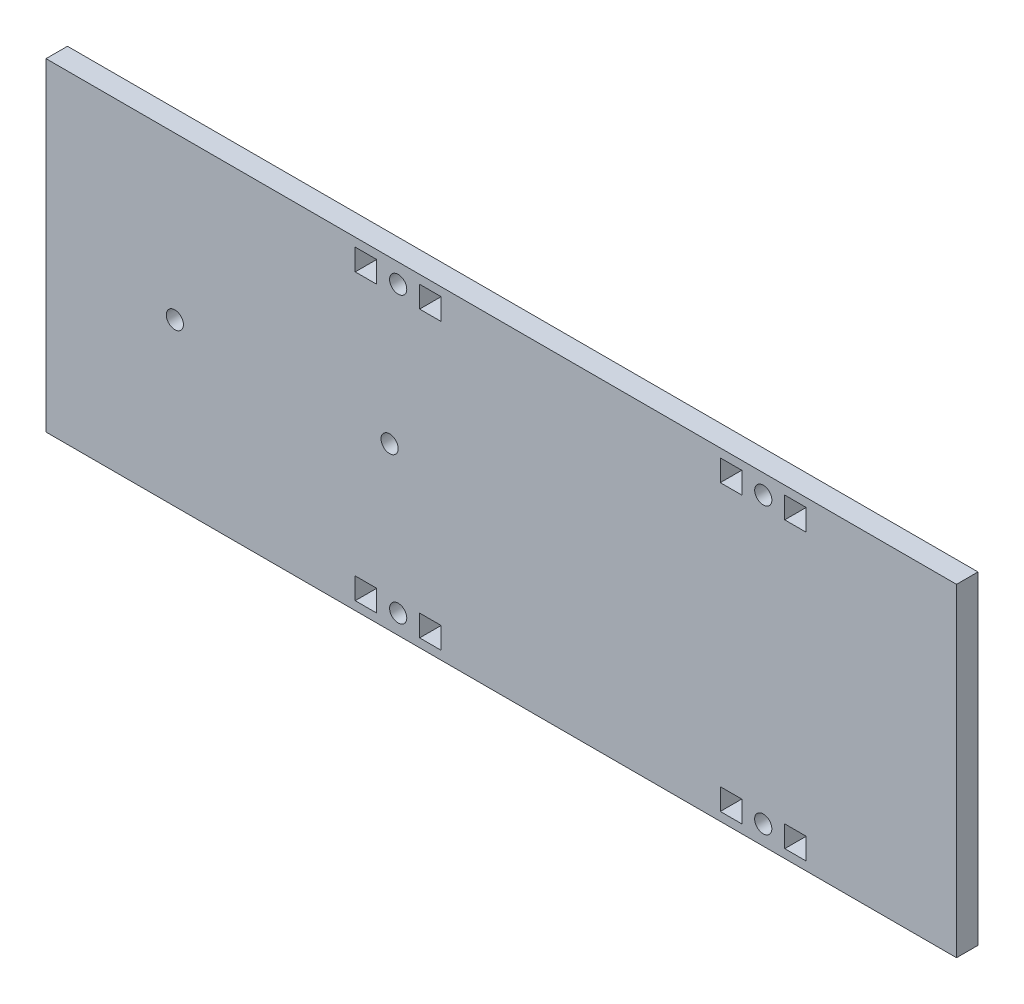
SolidWorks part; units mm, degrees
ref_plane "Plan de face" through (0, 0, 0) normal (0, 0, 1) x (1, 0, 0)
ref_plane "Plan de dessus" through (0, 0, 0) normal (0, 1, 0) x (1, 0, 0)
ref_plane "Plan de droite" through (0, 0, 0) normal (1, 0, 0) x (0, 0, -1)
sketch "Esquisse1" plane through (0, 0, 0) normal (0, 0, 1) x (1, 0, 0)
  line L0 (0, 0) -> (212, 0) construction
  line L1 (0, 37.65) -> (212, 37.65)
  line L2 (212, 37.65) -> (212, -37.65)
  line L3 (0, 37.65) -> (0, -37.65)
  line L4 (0, -37.65) -> (212, -37.65)
  circle A0 centre (30, 0) radius 2
  circle A1 centre (80, 0) radius 2
  point P11 (0, 0)
  line B0 (77, 33.15) -> (87, 33.15) construction
  line B1 (77, 35.65) -> (72, 35.65)
  line B2 (77, 35.65) -> (77, 30.65)
  line B3 (77, 30.65) -> (72, 30.65)
  line B4 (72, 35.65) -> (72, 30.65)
  line B5 (87, 35.65) -> (92, 35.65)
  line B6 (87, 35.65) -> (87, 30.65)
  line B7 (87, 30.65) -> (92, 30.65)
  line B8 (92, 35.65) -> (92, 30.65)
  line B9 (82, 33.15) -> (82, 40.1224) construction
  circle B10 centre (82, 33.15) radius 2
  line B11 (162, 33.15) -> (172, 33.15) construction
  line B12 (162, 35.65) -> (157, 35.65)
  line B13 (162, 35.65) -> (162, 30.65)
  line B14 (162, 30.65) -> (157, 30.65)
  line B15 (157, 35.65) -> (157, 30.65)
  line B16 (172, 35.65) -> (177, 35.65)
  line B17 (172, 35.65) -> (172, 30.65)
  line B18 (172, 30.65) -> (177, 30.65)
  line B19 (177, 35.65) -> (177, 30.65)
  line B20 (167, 33.15) -> (167, 40.1224) construction
  circle B21 centre (167, 33.15) radius 2
  line B22 (162, -35.65) -> (157, -35.65)
  line B23 (162, -35.65) -> (162, -30.65)
  line B24 (162, -30.65) -> (157, -30.65)
  line B25 (157, -35.65) -> (157, -30.65)
  line B26 (172, -35.65) -> (177, -35.65)
  line B27 (172, -35.65) -> (172, -30.65)
  line B28 (172, -30.65) -> (177, -30.65)
  line B29 (177, -35.65) -> (177, -30.65)
  circle B30 centre (167, -33.15) radius 2
  line B31 (77, -35.65) -> (72, -35.65)
  line B32 (77, -35.65) -> (77, -30.65)
  line B33 (77, -30.65) -> (72, -30.65)
  line B34 (72, -35.65) -> (72, -30.65)
  line B35 (87, -35.65) -> (92, -35.65)
  line B36 (87, -35.65) -> (87, -30.65)
  line B37 (87, -30.65) -> (92, -30.65)
  line B38 (92, -35.65) -> (92, -30.65)
  circle B39 centre (82, -33.15) radius 2
  dimension "D7" = 4
  dimension "D8" = 30
  dimension "D1" = 85
  dimension "D2" = 45
  dimension "D3" = 2
  dimension "D4" = 212
  dimension "D5" = 33.15
  dimension "D6" = 50
sketch_block_instance "Trou M4 plots 5mm-1"
sketch_block "Trou M4 plots 5mm" parameters "D2"=4, "D1"=5, "D3"=5, "D4"=10
sketch_block_instance "Trou M4 plots 5mm-2"
sketch_block_instance "Trou M4 plots 5mm-4"
sketch_block_instance "Trou M4 plots 5mm-5"
extrude "Boss.-Extru.1" add sketch "Esquisse1" along normal blind 5
